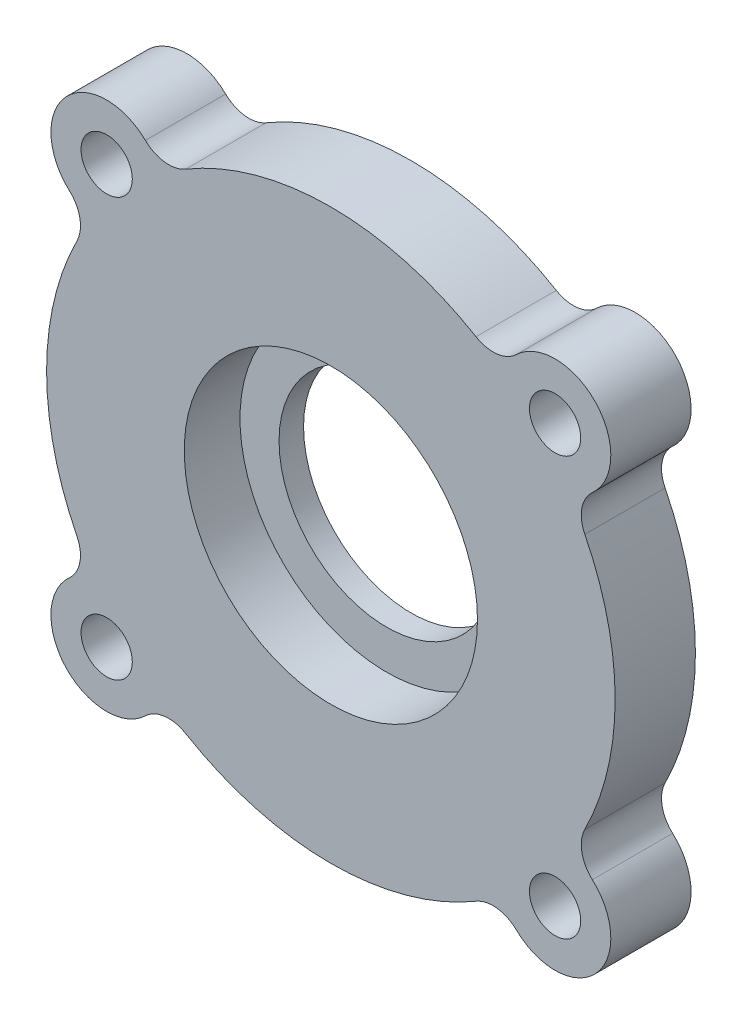
SolidWorks part; units mm, degrees
ref_plane "Спереди" through (0, 0, 0) normal (0, 0, 1) x (1, 0, 0)
ref_plane "Сверху" through (0, 0, 0) normal (0, 1, 0) x (1, 0, 0)
ref_plane "Справа" through (0, 0, 0) normal (1, 0, 0) x (0, 0, -1)
sketch "Эскиз1" plane through (0, 0, 0) normal (0, 0, 1) x (1, 0, 0)
  circle A25 centre (0, 0) radius 9.65
  circle A34 centre (-20.1122, -18.755) radius 2.3
  circle A35 centre (20.1122, -18.755) radius 2.3
  circle A36 centre (20.1122, 18.755) radius 2.3
  circle A37 centre (-20.1122, 18.755) radius 2.3
  arc A66 (16.6363, -22.3491) -> (23.4552, -15.0368) centre (20.1122, -18.755) ccw
  arc A67 (22.7808, -11.4579) -> (23.4552, -15.0368) centre (25.4609, -12.8059) ccw
  arc A68 (22.7808, -11.4579) -> (22.7808, 11.4579) centre (0, 0) ccw
  arc A69 (23.4552, 15.0368) -> (22.7808, 11.4579) centre (25.4609, 12.8059) ccw
  arc A70 (23.4552, 15.0368) -> (16.6363, 22.3491) centre (20.1122, 18.755) ccw
  arc A71 (13.0191, 21.9261) -> (16.6363, 22.3491) centre (14.5508, 24.5056) ccw
  arc A72 (13.0191, 21.9261) -> (-13.0191, 21.9261) centre (0, 0) ccw
  arc A73 (-16.6363, 22.3491) -> (-13.0191, 21.9261) centre (-14.5508, 24.5056) ccw
  arc A74 (-16.6363, 22.3491) -> (-23.4552, 15.0368) centre (-20.1122, 18.755) ccw
  arc A75 (-22.7808, 11.4579) -> (-23.4552, 15.0368) centre (-25.4609, 12.8059) ccw
  arc A76 (-22.7808, 11.4579) -> (-22.7808, -11.4579) centre (0, 0) ccw
  arc A77 (-23.4552, -15.0368) -> (-22.7808, -11.4579) centre (-25.4609, -12.8059) ccw
  arc A78 (-23.4552, -15.0368) -> (-16.6363, -22.3491) centre (-20.1122, -18.755) ccw
  arc A79 (-13.0191, -21.9261) -> (-16.6363, -22.3491) centre (-14.5508, -24.5056) ccw
  arc A80 (-13.0191, -21.9261) -> (13.0191, -21.9261) centre (0, 0) ccw
  arc A81 (16.6363, -22.3491) -> (13.0191, -21.9261) centre (14.5508, -24.5056) ccw
  dimension "D1" = 19.3
  dimension "D2" = 4.6
extrude "Бобышка-Вытянуть1" add sketch "Эскиз1" along normal blind 7.2
sketch "Эскиз3" plane through (0, 0, 7.2) normal (0, 0, 1) x (1, 0, 0)
  circle A0 centre (0, 0) radius 13.15
  dimension "D1" = 26.3
extrude "Вырез-Вытянуть2" cut sketch "Эскиз3" against normal blind 5
sketch "Эскиз4" plane through (0, 0, 0) normal (0, 0, -1) x (-1, 0, 0)
  circle A0 centre (0, 0) radius 18.8
  dimension "D1" = 37.6
extrude "Вырез-Вытянуть3" [suppressed] cut sketch "Эскиз4" against normal blind 0.2
